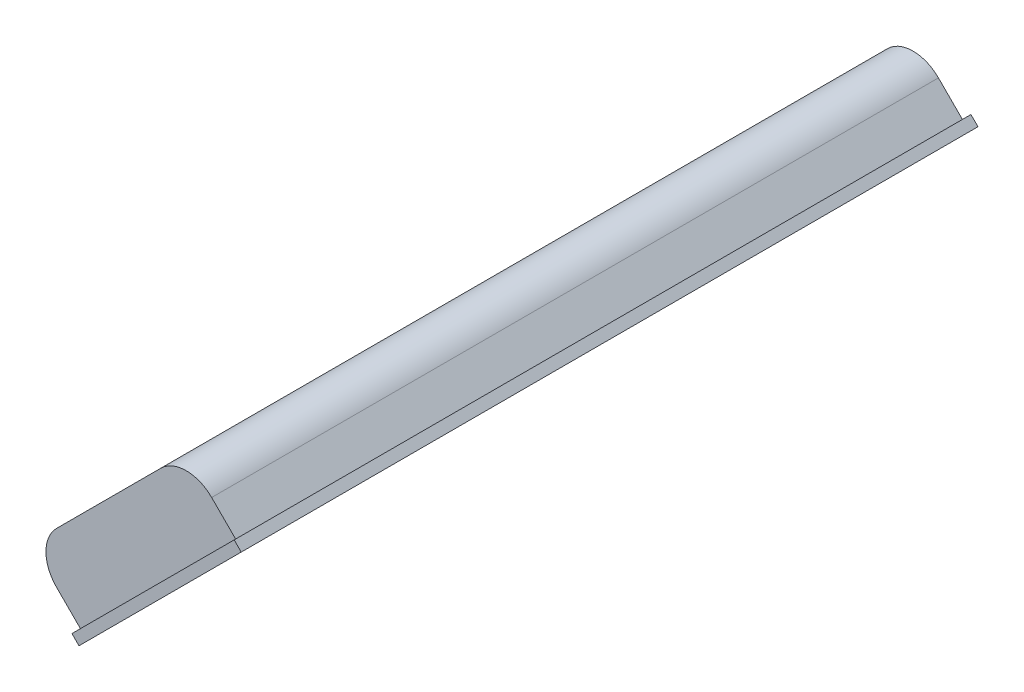
SolidWorks part; units mm, degrees
ref_plane "Front Plane" through (0, 0, 0) normal (0, 0, 1) x (1, 0, 0)
ref_plane "Top Plane" through (0, 0, 0) normal (0, 1, 0) x (1, 0, 0)
ref_plane "Right Plane" through (0, 0, 0) normal (1, 0, 0) x (0, 0, -1)
other "Configuration Table"
sketch "Sketch1" plane through (0, 0, 0) normal (0, 0, 1) x (1, 0, 0)
  line L0 (-193.7119, 287.05) -> (-287.05, 193.7119)
  line L1 (-287.05, 193.7119) -> (-305.7176, 212.3795)
  line L2 (-305.7176, 242.9265) -> (-242.9265, 305.7176)
  line L3 (-212.3795, 305.7176) -> (-193.7119, 287.05)
  arc A0 (-305.7176, 212.3795) -> (-305.7176, 242.9265) centre (-290.4441, 227.653) cw
  arc A1 (-242.9265, 305.7176) -> (-212.3795, 305.7176) centre (-227.653, 290.4441) cw
extrude "Cover" add sketch "Sketch1" along normal blind 437.1 from offset 397
sketch "Sketch2" plane through (0, 0, 0) normal (0, 0, 1) x (1, 0, 0)
  line L0 (-191.5906, 289.1713) -> (-289.1713, 191.5906)
  line L1 (-289.1713, 191.5906) -> (-293.414, 195.8332)
  line L2 (-293.414, 195.8332) -> (-195.8332, 293.414)
  line L3 (-195.8332, 293.414) -> (-191.5906, 289.1713)
extrude "Rail Flange" add sketch "Sketch2" along normal blind 443.1 from offset 400
